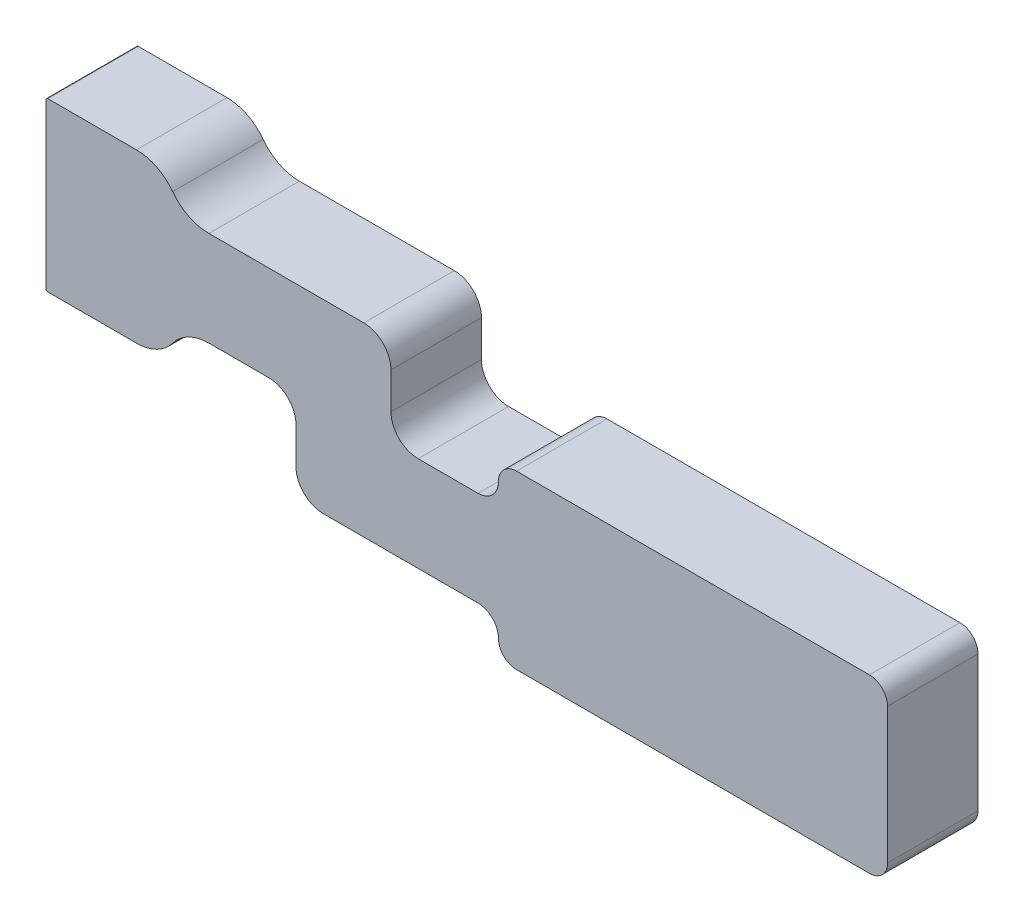
SolidWorks part; units mm, degrees
ref_plane "Front Plane" through (0, 0, 0) normal (1, 0, 0) x (0, 1, 0)
ref_plane "Top Plane" through (0, 0, 0) normal (0, 0, 1) x (0, 1, 0)
ref_plane "Right Plane" through (0, 0, 0) normal (0, 1, 0) x (-1, 0, 0)
sketch "Sketch1" plane through (0, 0, 0) normal (0, 0, 1) x (0, 1, 0)
  line L0 (-7.5, 4.25) -> (-9.5, 4.25) construction
  line L1 (-7.5, 43) -> (7.5, 43) construction
  line L2 (-9.5, 41) -> (-9.5, 2)
  line L3 (-7.5, 0) -> (7.5, 0)
  line L4 (9.5, 41) -> (9.5, 2)
  line L5 (-7.5, 4.25) -> (-7.5, 0) construction
  line L6 (7.5, 4.25) -> (9.5, 4.25) construction
  line L7 (-7.5, 39.25) -> (-7.5, 43) construction
  line L8 (-7.5, 4.25) -> (-2.5, 4.25) construction
  line L9 (-2.5, 4.25) -> (-2.5, 9.25) construction
  line L10 (4.75, 71.6875) -> (15.25, 71.6875) construction
  line L11 (8.25, 54.875) -> (12.25, 54.875)
  line L12 (5.25, 51.875) -> (5.25, 45.25)
  line L13 (1.75, 65.375) -> (-2.25, 65.375)
  line L14 (19.25, 83) -> (19.25, 92.8)
  line L15 (19.05, 93) -> (0.95, 93)
  line L16 (10, 93) -> (10, 75) construction
  line L17 (15.25, 57.875) -> (15.25, 75)
  line L18 (10, 75) -> (15.25, 75) construction
  line L19 (-5.25, 62.375) -> (-5.25, 45.25)
  line L20 (-5.25, 53.8125) -> (5.25, 53.8125) construction
  line L21 (-5.25, 53.8125) -> (-9.5, 53.8125) construction
  line L22 (-9.5, 53.8125) -> (-9.5, 43) construction
  line L23 (5.25, 53.8125) -> (9.5, 53.8125) construction
  line L24 (9.5, 53.8125) -> (9.5, 43) construction
  line L25 (0.75, 83) -> (0.75, 92.8)
  line L26 (4.75, 75) -> (4.75, 68.375)
  line L27 (10.25, 54.875) -> (10.25, 65.375) construction
  line L28 (0, 53.8125) -> (0, 43) construction
  line L29 (17.25, 79) -> (20.25, 75) construction
  line L30 (20.25, 75) -> (15.25, 75) construction
  line L31 (19.25, 83) -> (14.25, 83) construction
  line L32 (14.25, 83) -> (17.25, 79) construction
  circle A0 centre (-7.5, 4.25) radius 1.25 construction
  circle A1 centre (-2.5, 4.25) radius 1.25 construction
  circle A2 centre (2.5, 4.25) radius 1.25 construction
  circle A3 centre (7.5, 4.25) radius 1.25 construction
  circle A4 centre (-2.5, 9.25) radius 1.25 construction
  circle A5 centre (2.5, 9.25) radius 1.25 construction
  circle A6 centre (7.5, 9.25) radius 1.25 construction
  circle A7 centre (-2.5, 14.25) radius 1.25 construction
  circle A8 centre (2.5, 14.25) radius 1.25 construction
  circle A9 centre (7.5, 14.25) radius 1.25 construction
  circle A10 centre (-2.5, 19.25) radius 1.25 construction
  circle A11 centre (2.5, 19.25) radius 1.25 construction
  circle A12 centre (7.5, 19.25) radius 1.25 construction
  circle A13 centre (-2.5, 24.25) radius 1.25 construction
  circle A14 centre (2.5, 24.25) radius 1.25 construction
  circle A15 centre (7.5, 24.25) radius 1.25 construction
  circle A16 centre (-2.5, 29.25) radius 1.25 construction
  circle A17 centre (2.5, 29.25) radius 1.25 construction
  circle A18 centre (7.5, 29.25) radius 1.25 construction
  circle A19 centre (-2.5, 34.25) radius 1.25 construction
  circle A20 centre (2.5, 34.25) radius 1.25 construction
  circle A21 centre (7.5, 34.25) radius 1.25 construction
  circle A22 centre (-2.5, 39.25) radius 1.25 construction
  circle A23 centre (2.5, 39.25) radius 1.25 construction
  circle A24 centre (7.5, 39.25) radius 1.25 construction
  circle A25 centre (-7.5, 9.25) radius 1.25 construction
  circle A26 centre (-7.5, 14.25) radius 1.25 construction
  circle A27 centre (-7.5, 19.25) radius 1.25 construction
  circle A28 centre (-7.5, 24.25) radius 1.25 construction
  circle A29 centre (-7.5, 29.25) radius 1.25 construction
  circle A30 centre (-7.5, 34.25) radius 1.25 construction
  circle A31 centre (-7.5, 39.25) radius 1.25 construction
  arc A32 (5.25, 51.875) -> (8.25, 54.875) centre (8.25, 51.875) cw
  arc A33 (12.25, 54.875) -> (15.25, 57.875) centre (12.25, 57.875) ccw
  arc A34 (15.25, 75) -> (17.25, 79) centre (20.25, 75) cw
  arc A35 (17.25, 79) -> (19.25, 83) centre (14.25, 83) ccw
  arc A36 (4.75, 75) -> (2.75, 79) centre (-0.25, 75) ccw
  arc A37 (2.75, 79) -> (0.75, 83) centre (5.75, 83) cw
  arc A38 (1.75, 65.375) -> (4.75, 68.375) centre (1.75, 68.375) ccw
  arc A39 (-5.25, 62.375) -> (-2.25, 65.375) centre (-2.25, 62.375) cw
  arc A40 (-7.5, 43) -> (-9.5, 41) centre (-7.5, 41) ccw
  arc A41 (-9.5, 2) -> (-7.5, 0) centre (-7.5, 2) ccw
  arc A42 (7.5, 0) -> (9.5, 2) centre (7.5, 2) ccw
  arc A43 (7.5, 43) -> (9.5, 41) centre (7.5, 41) cw
  arc A44 (-5.25, 45.25) -> (-7.5, 43) centre (-7.5, 45.25) cw
  arc A45 (5.25, 45.25) -> (7.5, 43) centre (7.5, 45.25) ccw
  arc A46 (0.75, 92.8) -> (0.95, 93) centre (0.95, 92.8) cw
  arc A47 (19.25, 92.8) -> (19.05, 93) centre (19.05, 92.8) ccw
  point P0 (0, 0)
  point P121 (9.5, 0)
  point P126 (0.75, 93)
  point P131 (19.25, 93)
  dimension "D1" = 2.5
  dimension "D8" = 0.2
  dimension "D7" = 5
  dimension "D10" = 3
  dimension "D14" = 2
  dimension "D15" = 10
  dimension "D2" = 43
  dimension "D3" = 2
  dimension "D6" = 5
  dimension "D9" = 18.5
  dimension "D11" = 50
  dimension "D12" = 2.5
  dimension "D13" = 10.5
  dimension "D16" = 4.25
  dimension "D17" = 10.5
  dimension "D18" = 53.13
  dimension "D4" = 4
  dimension "D5" = 8
extrude "Boss-Extrude2" add sketch "Sketch1" along normal blind 10 contours L14 A47 L15 A46 L25 A37 A36 L26 A38 L13 A39 L19 A44 A40 L2 A41 L3 A42 L4 A43 A45 L12 A32 L11 A33 L17 A34 A35
